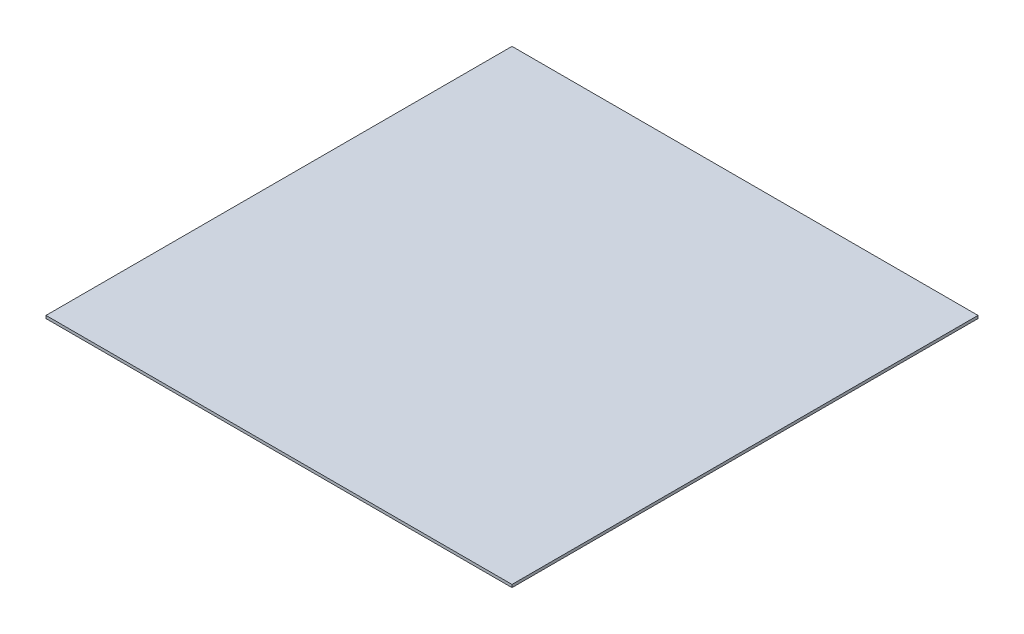
SolidWorks part; units mm, degrees
ref_plane "Front Plane" through (0, 0, 0) normal (0, 0, 1) x (1, 0, 0)
ref_plane "Top Plane" through (0, 0, 0) normal (0, 1, 0) x (1, 0, 0)
ref_plane "Right Plane" through (0, 0, 0) normal (1, 0, 0) x (0, 0, -1)
sketch "Sketch1" plane through (0, 0, 0) normal (0, 1, 0) x (1, 0, 0)
  line L1 (-12.5, -12.5) -> (12.5, -12.5)
  line L2 (-12.5, -12.5) -> (-12.5, 12.5)
  line L3 (-12.5, 12.5) -> (12.5, 12.5)
  line L4 (12.5, -12.5) -> (12.5, 12.5)
  line L5 (-12.5, -12.5) -> (12.5, 12.5) construction
  line L6 (-12.5, 12.5) -> (12.5, -12.5) construction
  point P0 (0, 0)
  dimension "D1" = 25
  dimension "D2" = 25
extrude "Boss-Extrude1" add sketch "Sketch1" along normal blind 0.15
